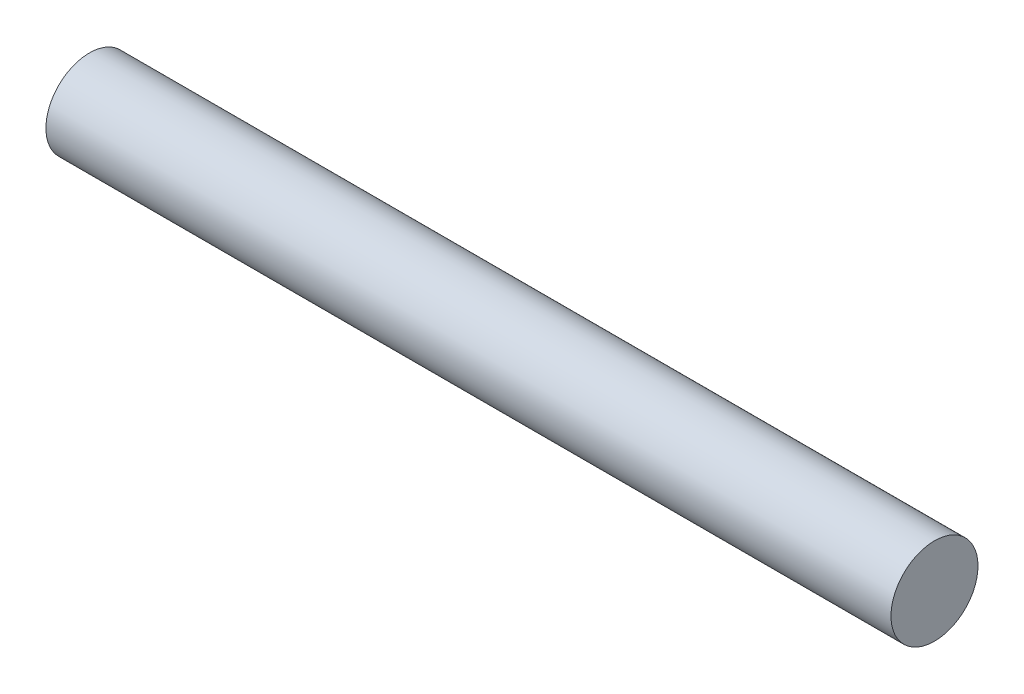
SolidWorks part; units mm, degrees
ref_plane "Front Plane" through (0, 0, 0) normal (0, 0, 1) x (1, 0, 0)
ref_plane "Top Plane" through (0, 0, 0) normal (0, 1, 0) x (1, 0, 0)
ref_plane "Right Plane" through (0, 0, 0) normal (1, 0, 0) x (0, 0, -1)
other "Configuration Table"
sketch "Sketch1" plane through (0, 0, 0) normal (1, 0, 0) x (0, 0, -1)
  circle A0 centre (0, 0) radius 19.05
  dimension "D1" = 38.1
extrude "Extrude1" add sketch "Sketch1" along normal mid plane 370
